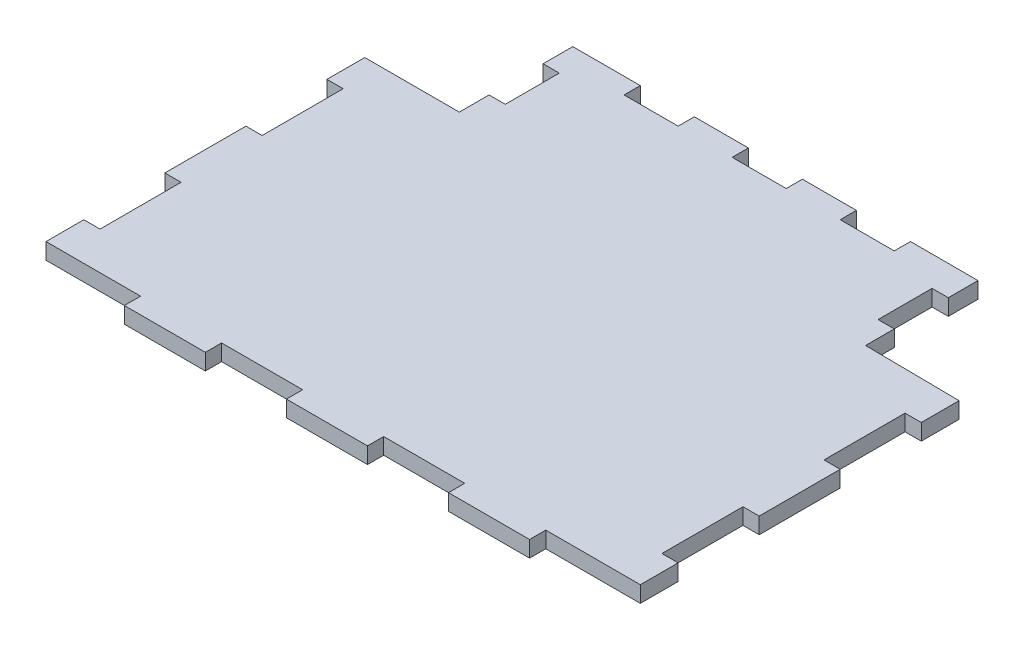
SolidWorks part; units mm, degrees
ref_plane "Alzado" through (0, 0, 0) normal (0, 0, 1) x (1, 0, 0)
ref_plane "Planta" through (0, 0, 0) normal (0, 1, 0) x (1, 0, 0)
ref_plane "Vista lateral" through (0, 0, 0) normal (1, 0, 0) x (0, 0, -1)
sketch "Croquis1" plane through (0, 0, 0) normal (0, 1, 0) x (1, 0, 0)
  line L0 (0, 3) -> (0, 10)
  line L1 (17.5, 0) -> (32.5, 0)
  line L2 (0, 62) -> (17.5, 62)
  line L3 (17.5, 62) -> (17.5, 67.5)
  line L4 (55, 0) -> (62.5, 0)
  line L5 (17.5, 83) -> (30, 83)
  line L6 (50, 80) -> (60, 80)
  line L7 (110, 62) -> (92.5, 62.1878)
  line L8 (110, 3) -> (110, 10)
  line L9 (62.5, 0) -> (62.5, 3)
  line L10 (62.5, 3) -> (77.5, 3)
  line L11 (77.5, 3) -> (77.5, 0)
  line L12 (77.5, 0) -> (92.5, 0)
  line L13 (92.5, 0) -> (92.5, 3)
  line L14 (92.5, 3) -> (110, 3)
  line L15 (20.5, 72.5) -> (20.5, 77.5)
  line L16 (17.5, 3) -> (0, 3)
  line L17 (17.5, 0) -> (17.5, 3)
  line L18 (32.5, 3) -> (32.5, 0)
  line L19 (47.5, 3) -> (32.5, 3)
  line L20 (47.5, 0) -> (47.5, 3)
  line L21 (110, 3) -> (110, 10)
  line L22 (110, 32.5) -> (110, 25)
  line L23 (110, 25) -> (107, 25)
  line L24 (107, 25) -> (107, 10)
  line L25 (107, 10) -> (110, 10)
  line L26 (0, 40) -> (3, 40)
  line L27 (107, 55) -> (110, 55)
  line L28 (107, 40) -> (107, 55)
  line L29 (110, 40) -> (107, 40)
  line L30 (3, 40) -> (3, 55)
  line L31 (3, 55) -> (0, 55)
  line L32 (3, 10) -> (0, 10)
  line L33 (3, 25) -> (3, 10)
  line L34 (0, 25) -> (3, 25)
  line L36 (20.5, 72.5) -> (20.5, 67.5)
  line L37 (20.5, 77.5) -> (17.5, 77.5)
  line L38 (20.5, 67.5) -> (17.5, 67.5)
  line L39 (17.5, 77.5) -> (17.5, 83)
  line L40 (70, 83) -> (60, 83)
  line L41 (50, 80) -> (50, 83)
  line L42 (50, 83) -> (40, 83)
  line L43 (40, 83) -> (40, 80)
  line L44 (40, 80) -> (30, 80)
  line L45 (30, 80) -> (30, 83)
  line L46 (80, 80) -> (80, 83)
  line L47 (70, 80) -> (80, 80)
  line L48 (70, 83) -> (70, 80)
  line L49 (60, 83) -> (70, 83)
  line L50 (60, 80) -> (60, 83)
  line L51 (92.5, 77.5) -> (92.5, 83)
  line L52 (89.5, 67.5) -> (92.5, 67.5)
  line L53 (89.5, 77.5) -> (92.5, 77.5)
  line L54 (40, 83) -> (50, 83)
  line L55 (89.5, 72.5) -> (89.5, 67.5)
  line L56 (89.5, 72.5) -> (89.5, 77.5)
  line L57 (0, 55) -> (0, 62)
  line L58 (0, 25) -> (0, 40)
  line L59 (77.5, 0) -> (92.5, 0)
  line L60 (47.5, 0) -> (62.5, 0)
  line L61 (110, 25) -> (110, 40)
  line L62 (110, 25) -> (110, 32.5)
  line L63 (110, 55) -> (110, 62)
  line L64 (92.5, 83) -> (80, 83)
  line L65 (92.5, 62) -> (92.5, 67.5)
  point P10 (55, 83)
  dimension "D3" = 17.5
  dimension "D4" = 21
  dimension "D5" = 7.5
  dimension "D6" = 3
  dimension "D7" = 15
  dimension "D8" = 15
  dimension "D10" = 7.5
  dimension "D11" = 3
  dimension "D12" = 15
  dimension "D14" = 5
  dimension "D16" = 5
  dimension "D17" = 7
  dimension "D19" = 10
  dimension "D20" = 10
extrude "Saliente-Extruir1" add sketch "Croquis1" along normal blind 3
